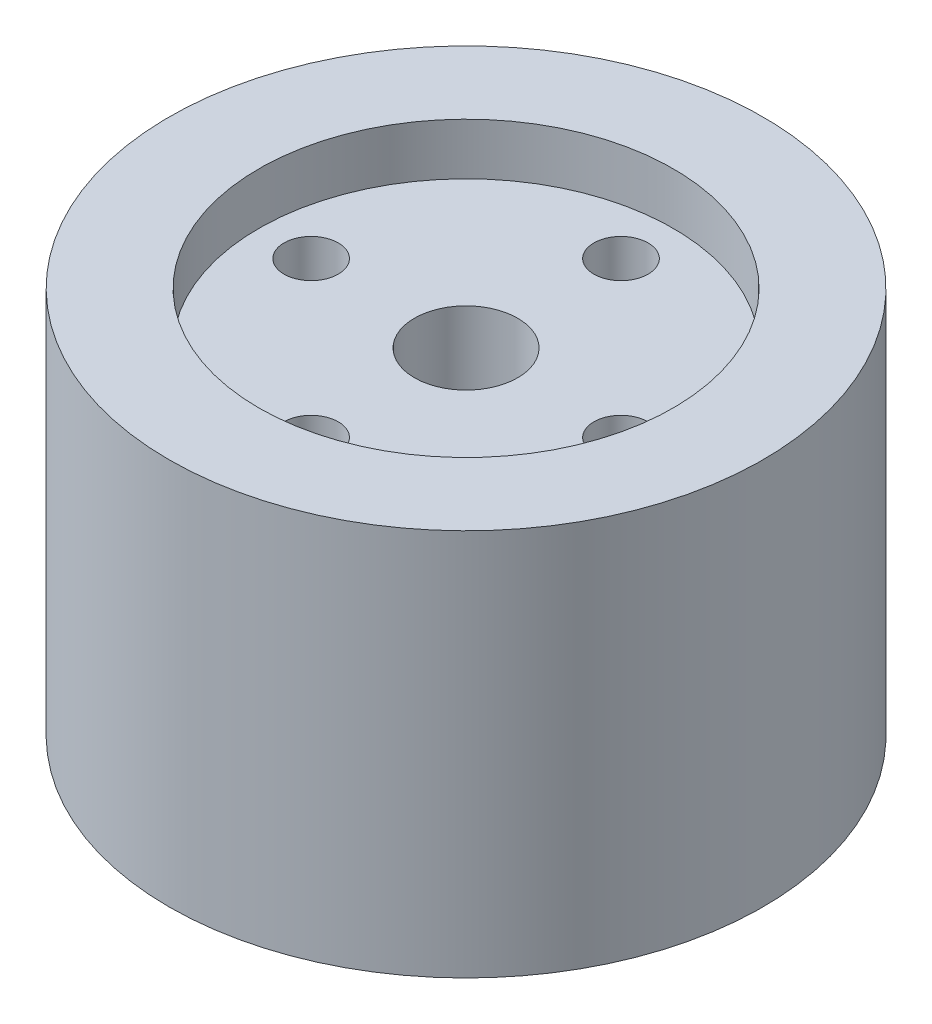
SolidWorks part; units mm, degrees
ref_plane "Front Plane" through (0, 0, 0) normal (0, 0, 1) x (1, 0, 0)
ref_plane "Top Plane" through (0, 0, 0) normal (0, 1, 0) x (1, 0, 0)
ref_plane "Right Plane" through (0, 0, 0) normal (1, 0, 0) x (0, 0, -1)
sketch "Sketch1" plane through (0, 0, 0) normal (0, 1, 0) x (1, 0, 0)
  line L0 (0, 0) -> (0, 12) construction
  circle A0 centre (0, 0) radius 23
  circle A1 centre (0, 0) radius 4
  circle A2 centre (0, 12) radius 2.1
  circle A3 centre (12, 0) radius 2.1
  circle A4 centre (0, -12) radius 2.1
  circle A5 centre (-12, 0) radius 2.1
  point P15 (0, 0)
  dimension "D1" = 46
  dimension "D2" = 8
  dimension "D4" = 4.2
  dimension "D3" = 12
  dimension "D5" = 4
extrude "Boss-Extrude1" add sketch "Sketch1" along normal blind 30
sketch "Sketch2" plane through (0, 30, 0) normal (0, 1, 0) x (1, 0, 0)
  circle A0 centre (0, 0) radius 16.05
  dimension "D1" = 32.1
extrude "Cut-Extrude1" cut sketch "Sketch2" against normal blind 4
sketch "Sketch3" plane through (0, 0, 0) normal (0, -1, 0) x (1, 0, 0)
  line L0 (12, -4.1569) -> (15.6, -2.0785)
  line L1 (4.1569, 12) -> (2.0785, 15.6)
  line L2 (2.0785, 15.6) -> (-2.0785, 15.6)
  line L3 (-2.0785, 15.6) -> (-4.1569, 12)
  line L4 (-4.1569, 12) -> (-2.0785, 8.4)
  line L5 (-2.0785, 8.4) -> (2.0785, 8.4)
  line L6 (2.0785, 8.4) -> (4.1569, 12)
  line L7 (15.6, -2.0785) -> (15.6, 2.0785)
  line L8 (15.6, 2.0785) -> (12, 4.1569)
  line L9 (12, 4.1569) -> (8.4, 2.0785)
  line L10 (8.4, 2.0785) -> (8.4, -2.0785)
  line L11 (8.4, -2.0785) -> (12, -4.1569)
  line L12 (-4.1569, -12) -> (-2.0785, -15.6)
  line L13 (-2.0785, -15.6) -> (2.0785, -15.6)
  line L14 (2.0785, -15.6) -> (4.1569, -12)
  line L15 (4.1569, -12) -> (2.0785, -8.4)
  line L16 (2.0785, -8.4) -> (-2.0785, -8.4)
  line L17 (-2.0785, -8.4) -> (-4.1569, -12)
  line L18 (-12, 4.1569) -> (-15.6, 2.0785)
  line L19 (-15.6, 2.0785) -> (-15.6, -2.0785)
  line L20 (-15.6, -2.0785) -> (-12, -4.1569)
  line L21 (-12, -4.1569) -> (-8.4, -2.0785)
  line L22 (-8.4, -2.0785) -> (-8.4, 2.0785)
  line L23 (-8.4, 2.0785) -> (-12, 4.1569)
  circle A0 centre (0, 12) radius 3.6 construction
  point P30 (0, 0)
  dimension "D1" = 7.2
  dimension "D2" = 4
extrude "Cut-Extrude2" cut sketch "Sketch3" against normal blind 12
